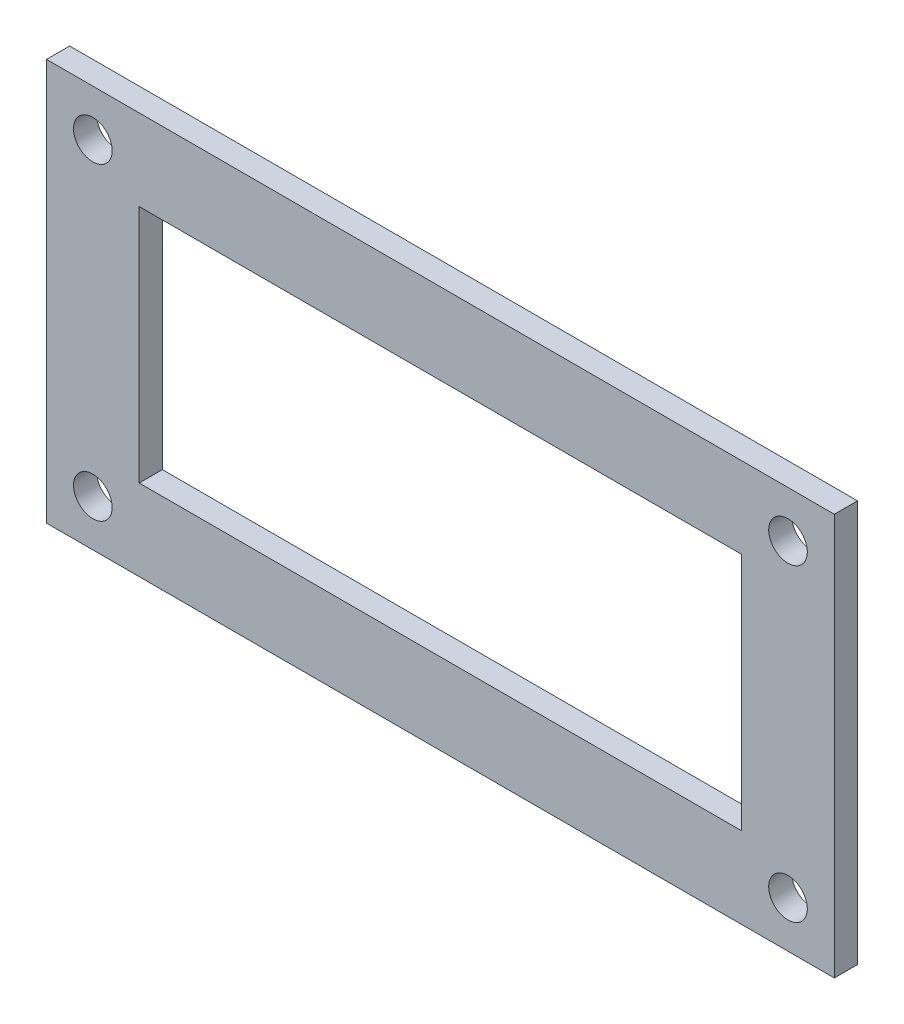
SolidWorks part; units mm, degrees
ref_plane "Front Plane" through (0, 0, 0) normal (0, 0, 1) x (1, 0, 0)
ref_plane "Top Plane" through (0, 0, 0) normal (0, 1, 0) x (1, 0, 0)
ref_plane "Right Plane" through (0, 0, 0) normal (1, 0, 0) x (0, 0, -1)
sketch "Sketch1" plane through (0, 0, 0) normal (0, 0, 1) x (1, 0, 0)
  line L5 (-51, -26) -> (51, -26)
  line L6 (-51, -26) -> (-51, 26)
  line L7 (-39, -15.5) -> (39, -15.5)
  line L8 (-39, -15.5) -> (-39, 15.5)
  line L9 (-39, 15.5) -> (39, 15.5)
  line L10 (39, -15.5) -> (39, 15.5)
  line L11 (-39, -15.5) -> (39, 15.5) construction
  line L12 (-39, 15.5) -> (39, -15.5) construction
  line L13 (-51, 26) -> (51, 26)
  line L14 (51, -26) -> (51, 26)
  line L15 (-51, -26) -> (51, 26) construction
  line L16 (-51, 26) -> (51, -26) construction
  point P0 (0, 0)
  point P1 (0, 0)
  point P6 (0, 0)
  dimension "D1" = 31
  dimension "D2" = 78
  dimension "D3" = 102
  dimension "D4" = 52
extrude "Boss-Extrude1" add sketch "Sketch1" along normal blind 3
sketch "Sketch2" plane through (0, 0, 0) normal (0, 0, 1) x (1, 0, 0)
  line L0 (51, 26) -> (-51, 26) construction
  line L1 (-51, 26) -> (-51, -26) construction
  line L2 (0, 0) -> (0, 32.4997) construction
  line L3 (-25.6787, 0) -> (22.563, 0) construction
  circle A0 centre (-45, 20) radius 2.5
  circle A1 centre (-45, -20) radius 2.5
  circle A2 centre (45, -20) radius 2.5
  circle A3 centre (45, 20) radius 2.5
  dimension "D1" = 5
  dimension "D2" = 6
  dimension "D3" = 6
extrude "Cut-Extrude6" cut sketch "Sketch2" along direction (0, 0, -1) on the side of the normal blind 31
